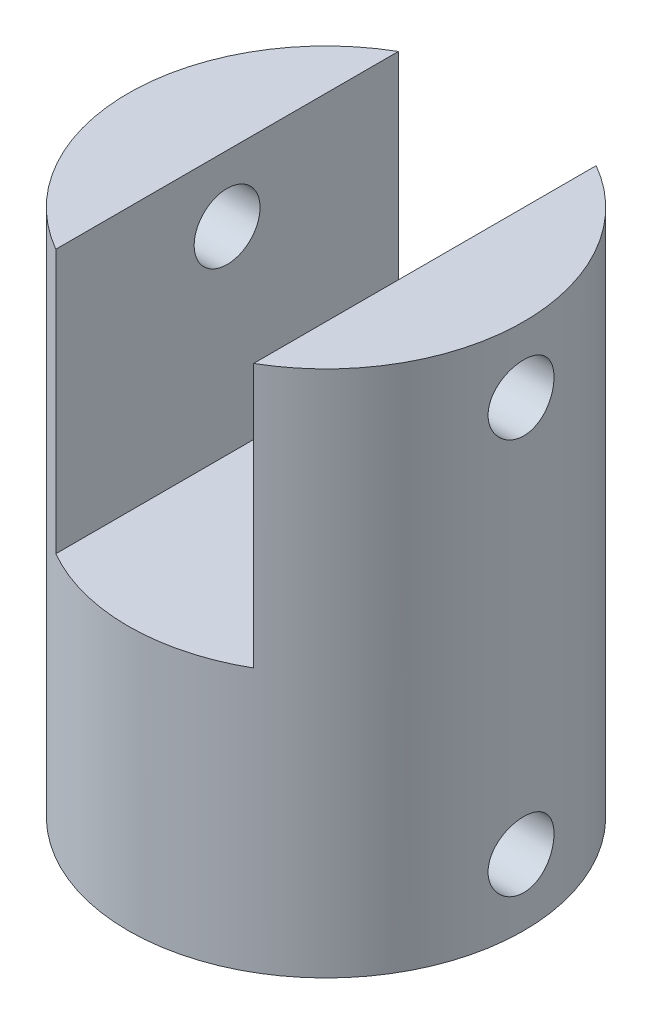
SolidWorks part; units mm, degrees
ref_plane "Front Plane" through (0, 0, 0) normal (0, 0, 1) x (1, 0, 0)
ref_plane "Top Plane" through (0, 0, 0) normal (0, 1, 0) x (1, 0, 0)
ref_plane "Right Plane" through (0, 0, 0) normal (1, 0, 0) x (0, 0, -1)
sketch "Sketch1" plane through (0, 0, 0) normal (0, 1, 0) x (1, 0, 0)
  circle A0 centre (0, 0) radius 30
  circle A1 centre (0, 0) radius 15
  dimension "D1" = 30
  dimension "D2" = 60
extrude "Boss-Extrude1" add sketch "Sketch1" along normal blind 80
sketch "Sketch2" plane through (0, 80, 0) normal (0, 1, 0) x (1, 0, 0)
  line L1 (-15, -30) -> (15, -30)
  line L2 (-15, -30) -> (-15, 30)
  line L3 (-15, 30) -> (15, 30)
  line L4 (15, -30) -> (15, 30)
  line L5 (-15, -30) -> (15, 30) construction
  line L6 (-15, 30) -> (15, -30) construction
  circle A0 centre (0, 0) radius 30 construction
  circle A1 centre (0, 0) radius 15 construction
  point P0 (0, 0)
extrude "Cut-Extrude1" cut sketch "Sketch2" against normal blind 40
sketch "Sketch3" plane through (-15, 0, 0) normal (1, 0, 0) x (0, 0, -1)
  line L1 (25.9808, 80) -> (-25.9808, 80) construction
  circle A0 centre (0, 70) radius 5
  dimension "D1" = 10
  dimension "D2" = 10
extrude "Cut-Extrude2" cut sketch "Sketch3" against normal through all both and the other way through all
sketch "Sketch4" plane through (0, 40, 0) normal (0, 1, 0) x (1, 0, 0)
  circle A0 centre (0, 0) radius 15
  arc A1 (15, 0) -> (-15, 0) centre (0, 0) ccw construction
extrude "Boss-Extrude2" add sketch "Sketch4" against normal blind 10
sketch "Sketch5" plane through (0, 0, 0) normal (1, 0, 0) x (0, 0, -1)
  line L0 (-30, 0) -> (30, 0) construction
  circle A0 centre (0, 10) radius 5
  dimension "D2" = 10
  dimension "D1" = 10
extrude "Cut-Extrude3" cut sketch "Sketch5" against normal through all both and the other way through all
sketch "Sketch6" plane through (-15, 0, 0) normal (1, 0, 0) x (0, 0, -1)
  line L4 (25.9808, 40) -> (25.9808, 80)
  line L5 (25.9808, 80) -> (-25.9808, 80)
  line L6 (-25.9808, 80) -> (-25.9808, 40)
  line L7 (-25.9808, 40) -> (25.9808, 40)
  line L8 (25.9808, 40) -> (25.9808, 80)
  line L9 (25.9808, 80) -> (-25.9808, 80)
  line L10 (-25.9808, 80) -> (-25.9808, 40)
  line L11 (-25.9808, 40) -> (25.9808, 40)
  circle A0 centre (0, 70) radius 5 construction
  circle A1 centre (0, 70) radius 5
  dimension "D1" = 0
